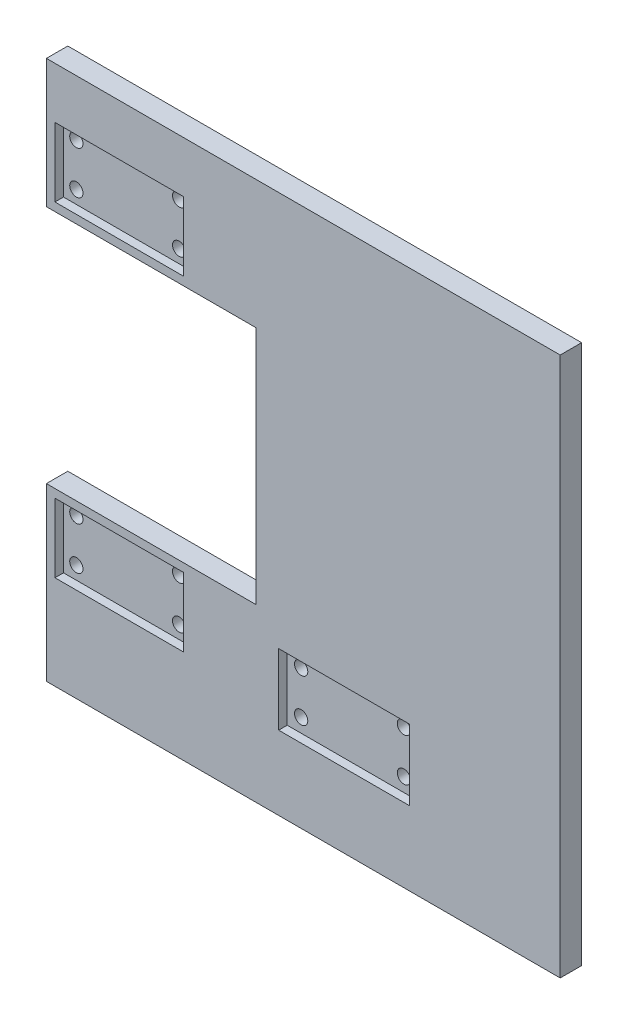
SolidWorks part; units mm, degrees
ref_plane "前视基准面" through (0, 0, 0) normal (0, 0, 1) x (1, 0, 0)
ref_plane "上视基准面" through (0, 0, 0) normal (0, 1, 0) x (1, 0, 0)
ref_plane "右视基准面" through (0, 0, 0) normal (1, 0, 0) x (0, 0, -1)
other "Configuration Table"
sketch "草图1" plane through (0, 0, 0) normal (0, 0, 1) x (1, 0, 0)
  line L0 (0, 0) -> (0, 30)
  line L1 (0, 30) -> (120, 30)
  line L2 (120, 30) -> (120, -96)
  line L3 (120, -96) -> (0, -96)
  line L4 (0, -96) -> (0, -56)
  line L5 (0, -56) -> (45, -56)
  line L6 (45, -56) -> (45, 0)
  line L7 (45, 0) -> (0, 0)
  dimension "D1" = 30
  dimension "D2" = 56
  dimension "D3" = 40
  dimension "D4" = 45
  dimension "D5" = 120
  dimension "D6" = 120
extrude "凸台-拉伸2" add sketch "草图1" along normal blind 5
sketch "草图3" plane through (0, 0, 5) normal (0, 0, 1) x (1, 0, 0)
  line L0 (0, 0) -> (0, 10)
  line L1 (0, 30) -> (0, 0) construction
  line L2 (0, 10) -> (17, 10)
  line L3 (-955, -28) -> (49045, -28) construction
  line L4 (2, 1.95) -> (32, 1.95)
  line L5 (2, 1.95) -> (2, 18.05)
  line L6 (2, 18.05) -> (32, 18.05)
  line L7 (32, 1.95) -> (32, 18.05)
  line L8 (2, 1.95) -> (32, 18.05) construction
  line L9 (2, 18.05) -> (32, 1.95) construction
  line L10 (45, 0) -> (45, -56) construction
  line L11 (2, -74.05) -> (32, -57.95) construction
  line L12 (2, -57.95) -> (32, -74.05) construction
  line L13 (32, -57.95) -> (32, -74.05)
  line L14 (2, -74.05) -> (32, -74.05)
  line L15 (2, -57.95) -> (2, -74.05)
  line L16 (2, -57.95) -> (32, -57.95)
  line L17 (0, -66) -> (17, -66)
  line L18 (0, -56) -> (0, -66)
  point P15 (45, -28)
  dimension "D1" = 10
  dimension "D2" = 17
  dimension "D3" = 16.1
  dimension "D4" = 30
extrude "切除-拉伸1" cut sketch "草图3" against normal blind 2
sketch "草图4" plane through (0, 0, 3) normal (0, 0, 1) x (1, 0, 0)
  line L0 (2, 18.05) -> (17, 18.05)
  line L5 (2, 18.05) -> (32, 18.05) construction
  line L6 (17, 18.05) -> (17, 10)
  line L7 (-998, 10) -> (49002, 10) construction
  line L8 (2, 2) -> (32, 2)
  line L9 (2, 2) -> (2, 18)
  line L10 (2, 18) -> (32, 18)
  line L11 (32, 2) -> (32, 18)
  line L12 (2, 2) -> (32, 18) construction
  line L13 (2, 18) -> (32, 2) construction
  line L14 (2, 18) -> (5, 18)
  line L15 (2, 18) -> (2, 15)
  line L16 (2, 15) -> (5, 15)
  line L17 (5, 18) -> (5, 15)
  line L18 (-955, -28) -> (49045, -28) construction
  line L19 (45, 0) -> (45, -56) construction
  circle A0 centre (5, 15) radius 1.55
  circle A1 centre (29, 15) radius 1.55
  circle A2 centre (29, 5) radius 1.55
  circle A3 centre (5, 5) radius 1.55
  circle A4 centre (5, -61) radius 1.55
  circle A5 centre (29, -61) radius 1.55
  circle A6 centre (29, -71) radius 1.55
  circle A7 centre (5, -71) radius 1.55
  point P20 (2, 10)
  point P29 (45, -28)
  dimension "D5" = 3.1
  dimension "D1" = 30
  dimension "D2" = 16
  dimension "D3" = 3
  dimension "D4" = 3
extrude "切除-拉伸2" cut sketch "草图4" against normal up to next contours A1 | A2 | L16 A0 L17 | L17 A0 L16 | A3 | A4 | A7 | A5 | A6
sketch "草图5" plane through (0, 0, 5) normal (0, 0, 1) x (1, 0, 0)
  line L0 (17, -74.05) -> (17, 18.05) construction
  line L1 (2, -74.05) -> (32, -74.05) construction
  line L2 (2, 18.05) -> (32, 18.05) construction
  line L3 (17, -74.05) -> (17, -85.05) construction
  line L4 (17, -85.05) -> (17, -96) construction
  line L5 (0, -96) -> (120, -96) construction
  line L6 (17, -96) -> (77, -96)
  line L7 (45, -56) -> (0, -56) construction
  line L8 (17, -56) -> (49, -56)
  line L9 (17, -56) -> (17, 0)
  line L10 (17, 0) -> (49, 0)
  line L11 (49, -56) -> (49, 0)
  dimension "D1" = 11
  dimension "D2" = 60
  dimension "D3" = 32
extrude "切除-拉伸3" cut sketch "草图5" against normal up to next contours L8 L11 L10 L9
sketch "草图7" plane through (0, 0, 5) normal (0, 0, 1) x (1, 0, 0)
  line L0 (49, -56) -> (59, -56)
  line L2 (59, -56) -> (99.5, -56)
  line L3 (59, -56) -> (59, -15.5)
  line L4 (59, -15.5) -> (99.5, -15.5)
  line L5 (99.5, -56) -> (99.5, -15.5)
  dimension "D1" = 10
  dimension "D2" = 40.5
  dimension "D3" = 40.5
extrude "凸台-拉伸4" add sketch "草图7" along normal blind 2 contours L2 L5 L4 L3
sketch "草图8" plane through (0, 0, 5) normal (0, 0, 1) x (1, 0, 0)
  line L0 (17, -998.05) -> (17, 49001.95) construction
  line L1 (2, 1.95) -> (32, 1.95) construction
  line L2 (59, -56) -> (69.5, -56)
  line L3 (59, -56) -> (99.5, -56) construction
  line L4 (69.5, -1056) -> (69.5, 48944) construction
  line L5 (69.5, -56) -> (69.5, -60.5)
  line L6 (69.5, -60.5) -> (69.5, -70.5)
  line L8 (54.25, -78.75) -> (84.75, -78.75)
  line L9 (54.25, -78.75) -> (54.25, -62.25)
  line L10 (54.25, -62.25) -> (84.75, -62.25)
  line L11 (84.75, -78.75) -> (84.75, -62.25)
  line L12 (54.25, -78.75) -> (84.75, -62.25) construction
  line L13 (54.25, -62.25) -> (84.75, -78.75) construction
  point P5 (17, 1.95)
  dimension "D1" = 10.5
  dimension "D2" = 4.5
  dimension "D3" = 10
  dimension "D4" = 30.5
  dimension "D5" = 16.5
extrude "切除-拉伸4" cut sketch "草图8" against normal blind 2
sketch "草图9" plane through (0, 0, 3) normal (0, 0, 1) x (1, 0, 0)
  line L0 (-945.75, -70.5) -> (49054.25, -70.5) construction
  line L1 (54.25, -62.25) -> (57.5, -62.25)
  line L2 (54.25, -62.25) -> (54.25, -65.5)
  line L3 (54.25, -65.5) -> (57.5, -65.5)
  line L4 (57.5, -62.25) -> (57.5, -65.5)
  line L5 (54.25, -78.75) -> (54.25, -62.25) construction
  line L6 (69.5, -1062.25) -> (69.5, 48937.75) construction
  line L7 (54.25, -62.25) -> (84.75, -62.25) construction
  circle A0 centre (57.5, -65.5) radius 1.55
  circle A1 centre (81.5, -65.5) radius 1.55
  circle A2 centre (81.5, -75.5) radius 1.55
  circle A3 centre (57.5, -75.5) radius 1.55
  point P11 (54.25, -70.5)
  point P16 (69.5, -62.25)
  dimension "D3" = 3.1
  dimension "D1" = 3.25
  dimension "D2" = 3.25
extrude "切除-拉伸6" cut sketch "草图9" against normal through all contours A1 | A0 | A3 | A2
sketch "草图10" plane through (0, 0, 7) normal (0, 0, 1) x (1, 0, 0)
  line L1 (59, -56) -> (119, -56)
  line L2 (59, -56) -> (59, -11)
  line L3 (59, -11) -> (119, -11)
  line L4 (119, -56) -> (119, -11)
  dimension "D1" = 60
  dimension "D2" = 45
extrude "凸台-拉伸5" add sketch "草图10" against normal blind 2
sketch "草图11" plane through (0, 0, 5) normal (0, 0, 1) x (1, 0, 0)
  line L1 (59, -11) -> (119, -11)
  line L2 (59, -11) -> (59, -56)
  line L3 (59, -56) -> (119, -56)
  line L4 (119, -11) -> (119, -56)
extrude "切除-拉伸8" cut sketch "草图11" along normal blind 2
